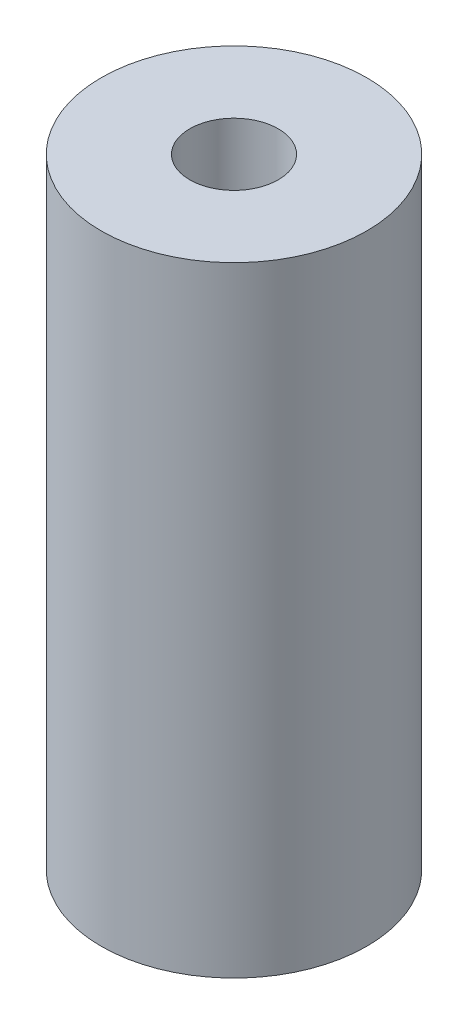
SolidWorks part; units mm, degrees
ref_plane "Front Plane" through (0, 0, 0) normal (0, 0, 1) x (1, 0, 0)
ref_plane "Top Plane" through (0, 0, 0) normal (0, 1, 0) x (1, 0, 0)
ref_plane "Right Plane" through (0, 0, 0) normal (1, 0, 0) x (0, 0, -1)
sketch "Sketch2" plane through (0, 0, 0) normal (0, 1, 0) x (1, 0, 0)
  circle A0 centre (0, 0) radius 3
  circle A1 centre (0, 0) radius 1
  dimension "D1" = 6
  dimension "D2" = 2
extrude "Boss-Extrude1" add sketch "Sketch2" along normal blind 14
